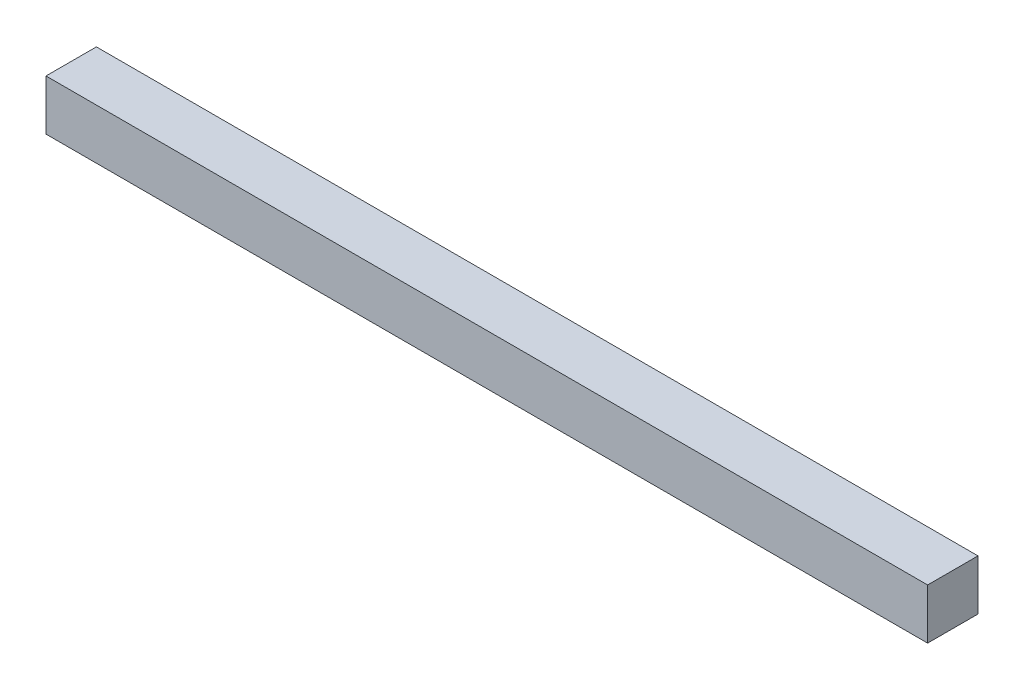
SolidWorks part; units mm, degrees
ref_plane "Front Plane" through (0, 0, 0) normal (0, 0, 1) x (1, 0, 0)
ref_plane "Top Plane" through (0, 0, 0) normal (0, 1, 0) x (1, 0, 0)
ref_plane "Right Plane" through (0, 0, 0) normal (1, 0, 0) x (0, 0, -1)
sketch "Sketch1" plane through (0, 0, 0) normal (1, 0, 0) x (0, 0, -1)
  line L1 (10, -10) -> (-10, -10)
  line L2 (10, -10) -> (10, 10)
  line L3 (10, 10) -> (-10, 10)
  line L4 (-10, -10) -> (-10, 10)
  line L5 (10, -10) -> (-10, 10) construction
  line L6 (10, 10) -> (-10, -10) construction
  point P0 (0, 0)
  dimension "D1" = 20
  dimension "D2" = 20
extrude "Boss-Extrude1" add sketch "Sketch1" along normal mid plane 350
